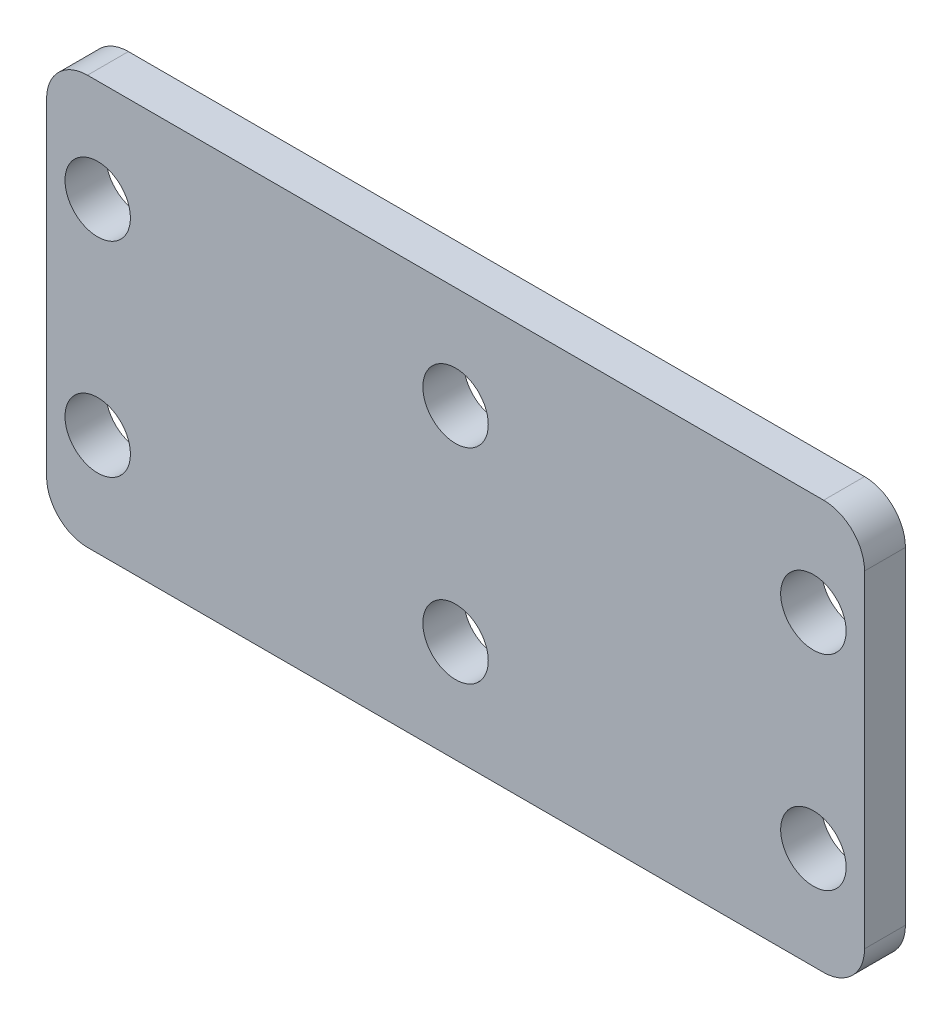
SolidWorks part; units mm, degrees
ref_plane "Front Plane" through (0, 0, 0) normal (0, 0, 1) x (1, 0, 0)
ref_plane "Top Plane" through (0, 0, 0) normal (0, 1, 0) x (1, 0, 0)
ref_plane "Right Plane" through (0, 0, 0) normal (1, 0, 0) x (0, 0, -1)
sketch "Sketch1" plane through (0, 0, 0) normal (0, 0, 1) x (1, 0, 0)
  line L1 (-20, 10) -> (20, 10)
  line L2 (-20, 10) -> (-20, -10)
  line L3 (-20, -10) -> (20, -10)
  line L4 (20, 10) -> (20, -10)
  line L5 (-20, 10) -> (20, -10) construction
  line L6 (-20, -10) -> (20, 10) construction
  point P0 (0, 0)
  dimension "D1" = 40
  dimension "D2" = 20
extrude "Boss-Extrude1" add sketch "Sketch1" along normal blind 2
hole_wizard "M3 Clearance Hole1" positions "Sketch2" profile "Sketch3" hole size "M3" standard "ANSI Metric" end condition through all
sketch "Sketch2" plane through (0, 0, 2) normal (0, 0, 1) x (1, 0, 0)
  line L1 (-17.5, 5) -> (17.5, 5)
  line L2 (-17.5, 5) -> (-17.5, -5)
  line L3 (-17.5, -5) -> (17.5, -5)
  line L4 (17.5, 5) -> (17.5, -5)
  line L5 (-17.5, 5) -> (17.5, -5) construction
  line L6 (-17.5, -5) -> (17.5, 5) construction
  line L10 (-20, -10) -> (20, -10) construction
  line L11 (20, 10) -> (-20, 10) construction
  point P2 (17.5, -5)
  point P25 (-17.5, 5)
  point P26 (-17.5, -5)
  point P27 (17.5, 5)
  point P42 (0, -10)
  point P43 (0, 0)
  point P55 (0, 5)
  point P57 (0, -5)
  dimension "D1" = 35
  dimension "D2" = 10
  dimension "D3" = 5
sketch "Sketch3" plane through (17.5, -5, 2) normal (1, 0, 0) x (0, -1, 0)
  line L0 (0, 0) -> (0, 2)
  line L1 (0, 2) -> (1.6, 2)
  line L2 (1.6, 2) -> (1.6, 0)
  line L5 (1.6, 0) -> (0, 0)
  line L11 (0, -6.35) -> (0, 107.95) construction
  dimension "Thru Hole Dia." = 3.2
  dimension "Thru Hole Depth" = 2
fillet "Fillet1" radius 2 4 edges at (20, -10, 1) (-20, -10, 1) (20, 10, 1) (-20, 10, 1)
